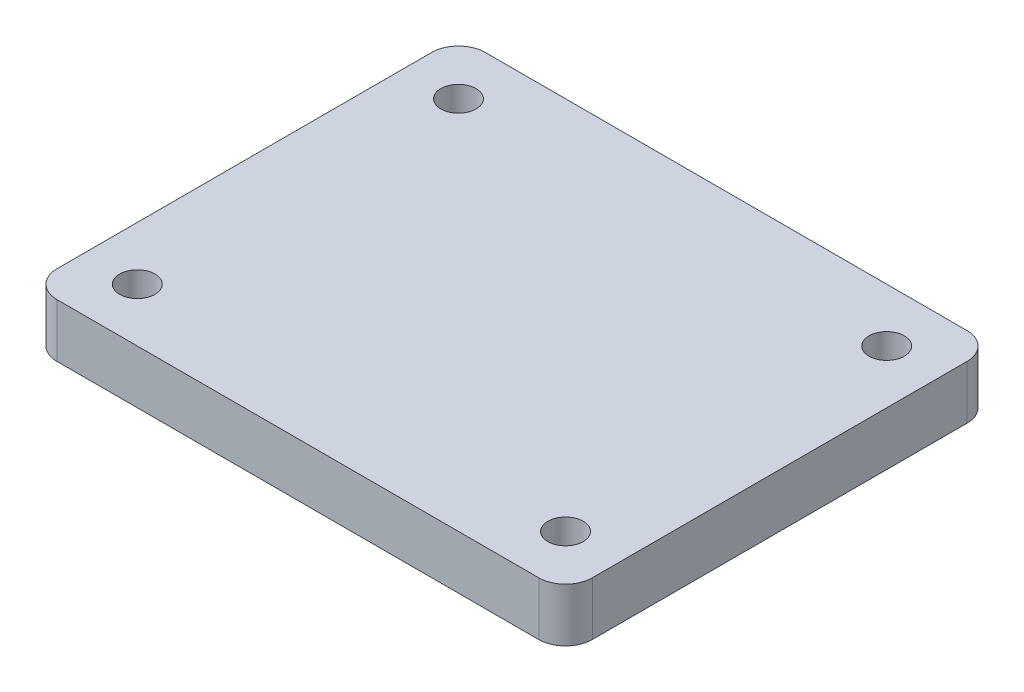
SolidWorks part; units mm, degrees
ref_plane "前基準面" through (0, 0, 0) normal (0, 0, 1) x (1, 0, 0)
ref_plane "上基準面" through (0, 0, 0) normal (0, 1, 0) x (1, 0, 0)
ref_plane "右基準面" through (0, 0, 0) normal (1, 0, 0) x (0, 0, -1)
sketch "草圖1" plane through (0, 0, 0) normal (0, 1, 0) x (1, 0, 0)
  line L1 (0, 0) -> (100, 0)
  line L2 (0, 0) -> (0, 80)
  line L3 (0, 80) -> (100, 80)
  line L4 (100, 0) -> (100, 80)
extrude "填料-伸長1" add sketch "草圖1" along normal blind 10
sketch "草圖2" plane through (0, 0, 0) normal (0, 1, 0) x (1, 0, 0)
  circle A0 centre (10, 10) radius 3.3
  circle A1 centre (90, 10) radius 3.3
  circle A2 centre (10, 70) radius 3.3
  circle A3 centre (90, 70) radius 3.3
extrude "除料-伸長1" cut sketch "草圖2" along normal through all
fillet "圓角1" radius 5 4 edges at (0, 5, -80) (100, 5, -80) (100, 5, 0) (0, 5, 0)
